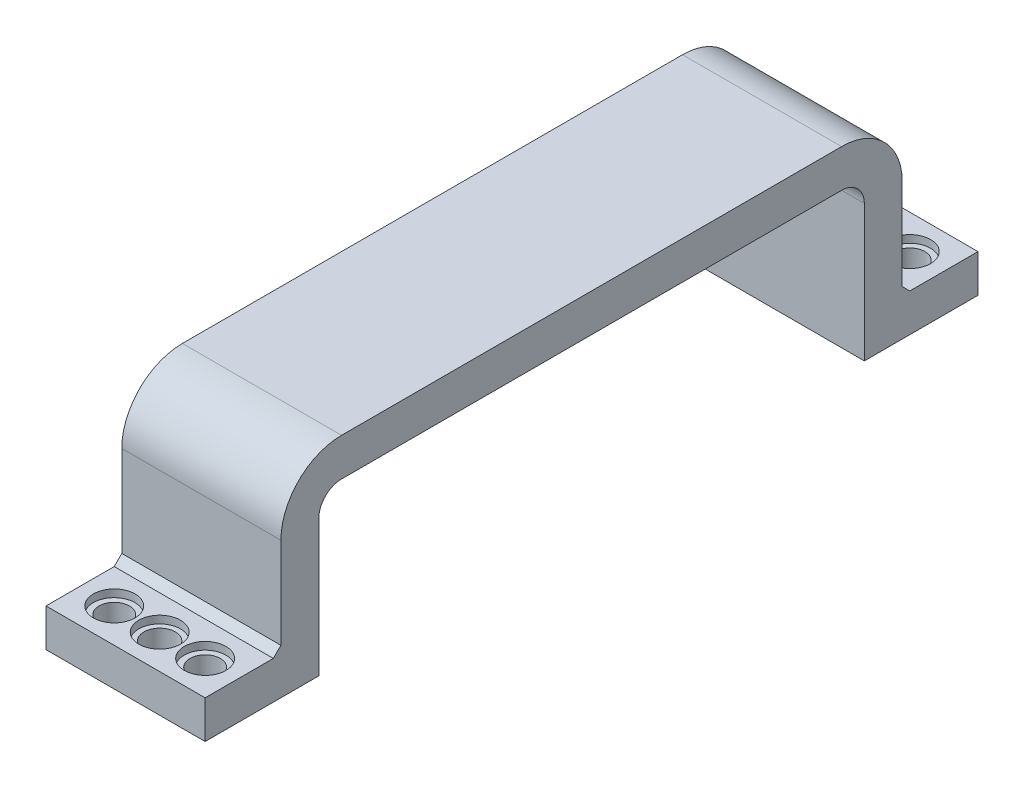
SolidWorks part; units mm, degrees
ref_plane "Alzado" through (0, 0, 0) normal (0, 0, 1) x (1, 0, 0)
ref_plane "Planta" through (0, 0, 0) normal (0, 1, 0) x (1, 0, 0)
ref_plane "Vista lateral" through (0, 0, 0) normal (1, 0, 0) x (0, 0, -1)
sketch "Croquis1" plane through (0, 0, 0) normal (1, 0, 0) x (0, 0, -1)
  line L0 (-51, 0) -> (-36, 0)
  line L1 (-36, 0) -> (-36, 18)
  line L2 (-33, 21) -> (33, 21)
  line L3 (0, 32.9286) -> (0, -17.3571) construction
  line L4 (36, 0) -> (36, 18)
  line L5 (51, 0) -> (36, 0)
  line L6 (-51, 0) -> (-51, 5)
  line L7 (-51, 5) -> (-42, 5)
  line L8 (-41, 6) -> (-41, 18)
  line L9 (-33, 26) -> (33, 26)
  line L10 (51, 0) -> (51, 5)
  line L11 (51, 5) -> (42, 5)
  line L12 (41, 6) -> (41, 18)
  line L13 (-42, 5) -> (-41, 6)
  line L14 (42, 5) -> (41, 6)
  arc A0 (-36, 18) -> (-33, 21) centre (-33, 18) cw
  arc A1 (36, 18) -> (33, 21) centre (33, 18) ccw
  arc A2 (-41, 18) -> (-33, 26) centre (-33, 18) cw
  arc A3 (41, 18) -> (33, 26) centre (33, 18) ccw
  point P10 (0, 21)
  point P16 (-41, 5)
  point P20 (41, 5)
  point P21 (-51, 2.5)
  point P24 (0, 26)
  point P25 (0, 0)
  dimension "D5" = 3
  dimension "D1" = 5
  dimension "D2" = 72
  dimension "D3" = 21
  dimension "D4" = 5
  dimension "D6" = 15
extrude "Saliente-Extruir1" add sketch "Croquis1" along normal blind 21
sketch "Croquis2" plane through (0, 26, 0) normal (0, 1, 0) x (1, 0, 0)
  line L0 (-10.0376, 0) -> (35.419, 0) construction
  circle A0 centre (10.5, 46.5) radius 2.75
  circle A1 centre (16.5, 46.5) radius 2.75
  circle A2 centre (4.5, 46.5) radius 2.75
  circle A3 centre (16.5, -46.5) radius 2.75
  circle A4 centre (10.5, -46.5) radius 2.75
  circle A5 centre (4.5, -46.5) radius 2.75
  point P8 (10.5, 46.5)
  point P10 (0, 0)
  point P11 (0, 0)
  dimension "D1" = 5.5
  dimension "5.5" = 5.5
  dimension "D5" = 5.5
  dimension "D3" = 6
  dimension "D2" = 6
extrude "Cortar-Extruir1" cut sketch "Croquis2" against normal blind 22
sketch "Croquis3" plane through (0, 4, 0) normal (0, 1, 0) x (1, 0, 0)
  line L0 (-19.6218, 0) -> (37.6096, 0) construction
  circle A0 centre (4.5, 46.5) radius 2
  circle A1 centre (10.5, 46.5) radius 2
  circle A2 centre (16.5, 46.5) radius 2
  circle A3 centre (4.5, -46.5) radius 1.9334
  circle A4 centre (10.5, -46.5) radius 2.0703
  circle A5 centre (16.5, -46.5) radius 1.9334
  circle A7 centre (10.5, -46.5) radius 2
  circle A8 centre (16.5, -46.5) radius 2
  circle A9 centre (4.5, -46.5) radius 2
  dimension "D1" = 4
  dimension "D2" = 4
  dimension "D3" = 4
extrude "Cortar-Extruir3" cut sketch "Croquis3" against normal blind 22
sketch "Croquis5" plane through (0, 4, 0) normal (0, 1, 0) x (1, 0, 0)
  circle A0 centre (4.5, -46.5) radius 1.9334
  circle A1 centre (10.5, -46.5) radius 2.0153
  circle A2 centre (16.5, -46.5) radius 1.9334
extrude "Cortar-Extruir4" cut sketch "Croquis5" against normal blind 22
